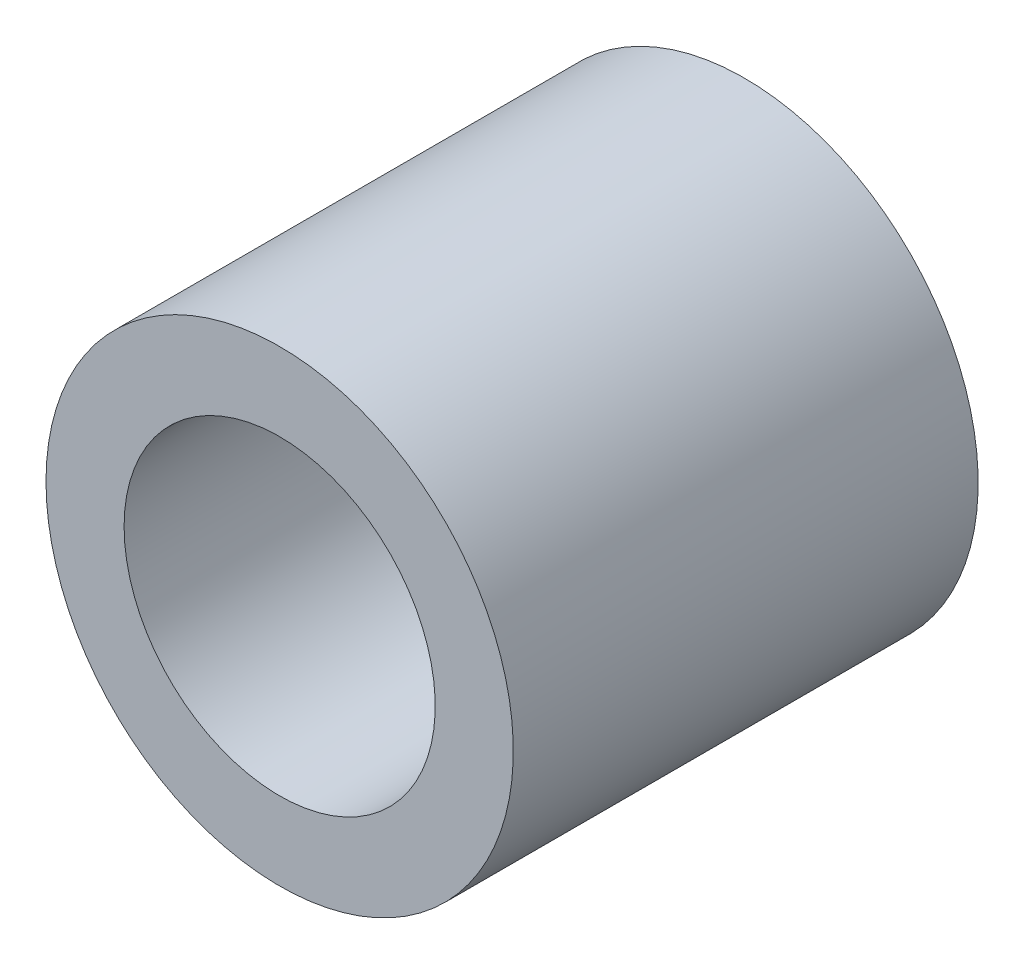
SolidWorks part; units mm, degrees
material "Commercial Bronze, UNS C22000 (90-10 Bronze)"
ref_plane "Front Plane" through (0, 0, 0) normal (0, 0, 1) x (1, 0, 0)
ref_plane "Top Plane" through (0, 0, 0) normal (0, 1, 0) x (1, 0, 0)
ref_plane "Right Plane" through (0, 0, 0) normal (1, 0, 0) x (0, 0, -1)
sketch "Sketch1" plane through (0, 0, 0) normal (0, 0, 1) x (1, 0, 0)
  circle A0 centre (0, 0) radius 4.7879
  circle A1 centre (0, 0) radius 3.1877
  dimension "D1" = 9.5758
  dimension "ID" = 6.3754
extrude "Extrude1" add sketch "Sketch1" along normal mid plane 9.525
sketch "Sketch2" plane through (0, 0, 0) normal (1, 0, 0) x (0, 0, -1)
  line L0 (-4.7625, -3.1877) -> (4.7625, -3.1877) construction
  line L3 (4.7625, 3.1877) -> (-4.7625, 3.1877) construction
  line L5 (-4.7625, -3.1877) -> (4.7625, -3.1877)
  line L6 (4.7625, 3.1877) -> (-4.7625, 3.1877)
sketch "Sketch4" plane through (0, 0, 4.7625) normal (0, 0, 1) x (1, 0, 0)
  line L0 (0, 0) -> (-2.254, 2.254)
  line L1 (0, -13.97) -> (0, 13.97) construction
  circle A0 centre (0, 0) radius 3.1877 construction
  dimension "D1" = 45
